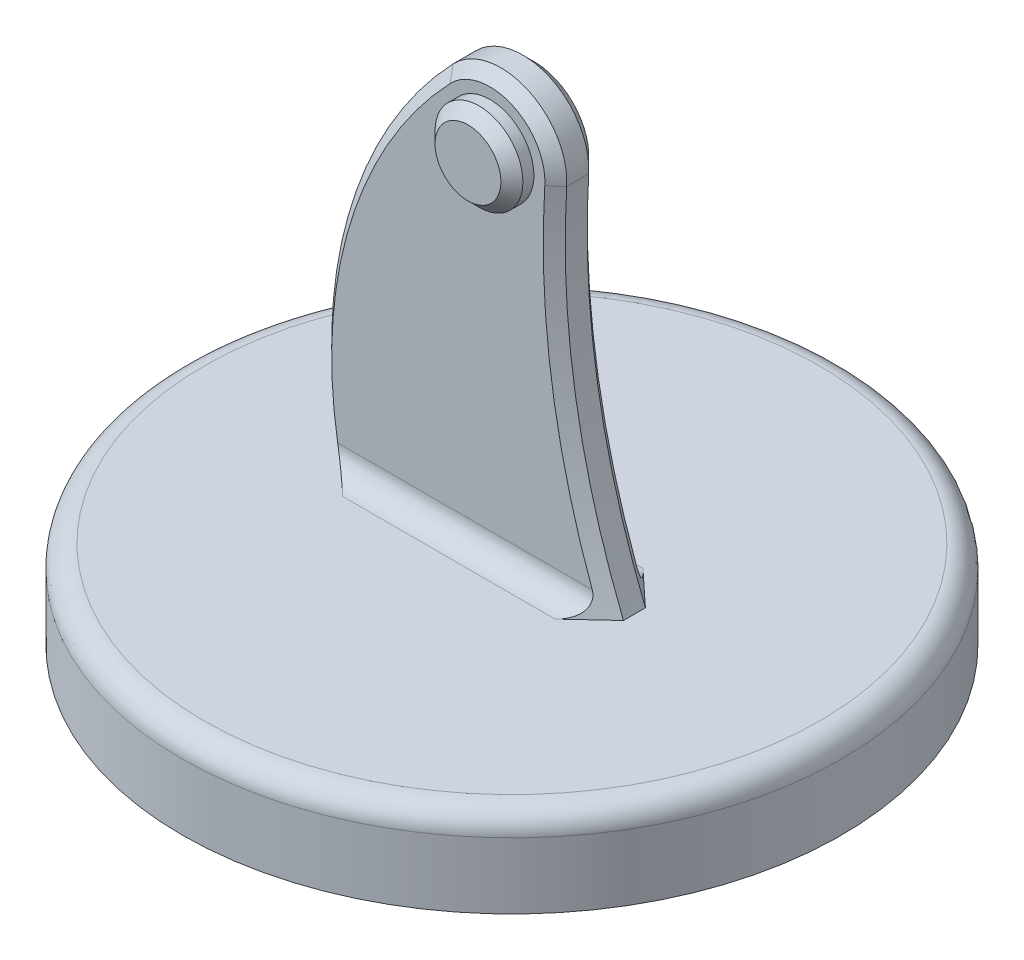
SolidWorks part; units mm, degrees
material "Plain Carbon Steel"
ref_plane "Front Plane" through (0, 0, 0) normal (0, 0, 1) x (1, 0, 0)
ref_plane "Top Plane" through (0, 0, 0) normal (0, 1, 0) x (1, 0, 0)
ref_plane "Right Plane" through (0, 0, 0) normal (1, 0, 0) x (0, 0, -1)
sketch "Sketch1" plane through (0, 0, 0) normal (0, 1, 0) x (1, 0, 0)
  circle A0 centre (0, 0) radius 75
  dimension "D1" = 150
extrude "Boss-Extrude1" add sketch "Sketch1" along normal blind 20
fillet "Fillet1" radius 5 1 edges at (0, 20, 75)
sketch "Sketch2" plane through (0, 0, 0) normal (0, 0, 1) x (1, 0, 0)
  line L0 (0, 0) -> (0, 100) construction
  line L1 (-75, 15) -> (75, 15) construction
  line L3 (-35, 15) -> (30, 15)
  arc A0 (14.9706, 99.062) -> (-10.8492, 110.3583) centre (0, 100) ccw
  arc A1 (-35, 15) -> (-10.8492, 110.3583) centre (61.4788, 41.3028) cw
  arc A2 (14.9706, 99.062) -> (30, 15) centre (194.6184, 87.8065) ccw
  dimension "D3" = 30
  dimension "D5" = 100
  dimension "D6" = 180
  dimension "D1" = 30
  dimension "D2" = 35
  dimension "D4" = 100
extrude "Boss-Extrude2" add sketch "Sketch2" along normal mid plane 10
chamfer "Chamfer1" distance 2.5 angle 45 6 edges at (-34.7965, 68.3412, 5) (6.0123, 113.7423, 5) (16.9703, 58.8038, 5) (-34.7965, 68.3412, -5) (6.0123, 113.7423, -5) (16.9703, 58.8038, -5)
fillet "Fillet2" radius 5 2 edges at (-4.2415, 20, -5) (-4.2415, 20, 5)
sketch "Sketch3" plane through (0, 0, 5) normal (0, 0, 1) x (1, 0, 0)
  circle A0 centre (0, 100) radius 10
  dimension "D1" = 20
extrude "Boss-Extrude3" add sketch "Sketch3" along normal blind 5
chamfer "Chamfer2" distance 2.5 angle 45 1 edges at (10, 100, 10)
sketch "Sketch4" plane through (0, 0, -5) normal (0, 0, -1) x (-1, 0, 0)
  circle A0 centre (0, 100) radius 5
  dimension "D1" = 10
extrude "Cut-Extrude1" cut sketch "Sketch4" against normal blind 10
